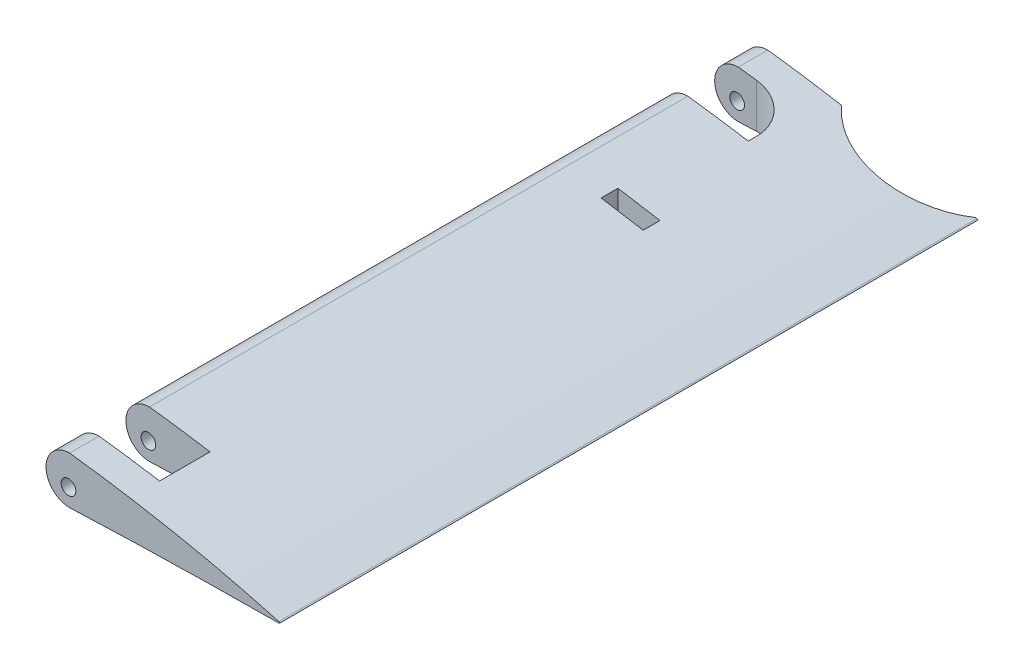
SolidWorks part; units mm, degrees
material "Balsa"
ref_plane "Front Plane" through (0, 0, 0) normal (0, 0, 1) x (1, 0, 0)
ref_plane "Top Plane" through (0, 0, 0) normal (0, 1, 0) x (1, 0, 0)
ref_plane "Right Plane" through (0, 0, 0) normal (1, 0, 0) x (0, 0, -1)
curve "曲線2"
  spline degree 3 poles (200, 0.26, 0) (196.6701, 1.1665, 0) (190.0264, 2.975, 0) (176.7171, 6.2635, 0) (160.0733, 9.8968, 0) (140.0541, 13.4784, 0) (120.0503, 16.4141, 0) (100.0354, 18.5082, 0) (80.0223, 19.8143, 0) (63.3151, 19.8275, 0) (49.9753, 18.9046, 0) (39.957, 17.689, 0) (29.917, 15.8963, 0) (21.5972, 13.7404, 0) (14.9301, 11.563, 0) (9.903, 9.5074, 0) (5.6136, 7.2843, 0) (1.8903, 4.6252, 0) (-1.3508, 0.3484, 0) (2.1476, -2.9224, 0) (5.7173, -4.2063, 0) (9.9686, -5.0729, 0) (14.9893, -5.5135, 0) (21.6639, -5.8253, 0) (30.0021, -5.8019, 0) (40.0043, -5.522, 0) (49.9995, -4.9891, 0) (63.3329, -4.3655, 0) (79.9968, -3.5653, 0) (100.0006, -2.8138, 0) (119.9979, -1.9794, 0) (139.9972, -1.2688, 0) (159.998, -0.746, 0) (176.6662, -0.4806, 0) (189.9997, -0.3058, 0) (196.6666, -0.2753, 0) (200, -0.26, 0) knots 0 0 0 0 0.025305 0.050488 0.10052 0.150191 0.199587 0.24874 0.297716 0.346601 0.371103 0.395726 0.42057 0.445825 0.458702 0.47192 0.485786 0.493461 0.506863 0.516148 0.522766 0.535269 0.547551 0.559786 0.584229 0.608681 0.633151 0.657622 0.706558 0.755482 0.804406 0.85332 0.902221 0.951113 0.975557 1 1 1 1
sketch "草圖4" plane through (0, 0, 0) normal (0, 0, 1) x (1, 0, 0)
  line L8 (26.3929, -5.7959) -> (118.9885, -5.7959) construction
  spline S1 degree 2 poles (120, 0.156) (120.5501, 0) (120, -0.156) knots 0 0 0 1 1 1
  spline S2 degree 3 poles (120, 0.156) (118.0021, 0.6999) (114.0158, 1.785) (106.0302, 3.7581) (96.044, 5.9381) (84.0324, 8.087) (72.0302, 9.8485) (60.0213, 11.1049) (48.0134, 11.8886) (37.9891, 11.8965) (29.9852, 11.3428) (23.9742, 10.6134) (17.9502, 9.5378) (12.9583, 8.2442) (8.9581, 6.9378) (5.9418, 5.7044) (3.3681, 4.3706) (1.1342, 2.7751) (-0.8105, 0.209) (1.2885, -1.7534) (3.4304, -2.5238) (5.9811, -3.0437) (8.9936, -3.3081) (12.9983, -3.4952) (18.0013, -3.4812) (24.0026, -3.3132) (29.9997, -2.9935) (37.9998, -2.6193) (47.9981, -2.1392) (60.0003, -1.6883) (71.9988, -1.1877) (83.9983, -0.7613) (95.9988, -0.4476) (105.9997, -0.2883) (113.9998, -0.1835) (118, -0.1652) (120, -0.156) knots 0 0 0 0 0.025305 0.050488 0.10052 0.150191 0.199587 0.24874 0.297716 0.346601 0.371103 0.395726 0.42057 0.445825 0.458702 0.47192 0.485786 0.493461 0.506863 0.516148 0.522766 0.535269 0.547551 0.559786 0.584229 0.608681 0.633151 0.657622 0.706558 0.755482 0.804406 0.85332 0.902221 0.951113 0.975557 1 1 1 1
extrude "填料-伸長1" add sketch "草圖4" along normal blind 185
sketch "草圖2" plane through (0, 0, 0) normal (0, 0, -1) x (-1, 0, 0)
  circle A0 centre (-25, 5) radius 3.25
  circle A1 centre (-50, 5) radius 3.25
  dimension "D1" = 6.5
  dimension "D2" = 25
  dimension "D3" = 25
  dimension "D4" = 5
extrude "除料-伸長1" cut sketch "草圖2" against normal through all
sketch "草圖3" plane through (0, 0, 0) normal (0, 1, 0) x (1, 0, 0)
  line L0 (120, 0) -> (-0.0337, 0) construction
  line L1 (70.275, -12) -> (120.275, -12)
  line L2 (70.275, -12) -> (70.275, -178)
  line L3 (70.275, -178) -> (120.275, -178)
  line L6 (-0.0337, -185) -> (120, -185) construction
  line L16 (120.275, -12) -> (166.4805, 19.3533)
  line L17 (166.4805, 19.3533) -> (-21.7711, 70.9334)
  line L18 (-21.7711, 70.9334) -> (-60.7316, -48.3616)
  line L19 (-60.7316, -48.3616) -> (-45.0232, -192.445)
  line L20 (-45.0232, -192.445) -> (84.8579, -230.5752)
  line L21 (84.8579, -230.5752) -> (139.8603, -200.5385)
  line L22 (139.8603, -200.5385) -> (120.275, -178)
  dimension "D1" = 12
  dimension "D3" = 7
extrude "除料-伸長2" cut sketch "草圖3" against normal through all and the other way through all
sketch "草圖5" plane through (0, 0, 178) normal (0, 0, 1) x (1, 0, 0)
  line L0 (70.275, 9.9794) -> (70.275, -1.2673)
  arc A0 (70.275, 9.9794) -> (70.275, -1.2673) centre (70.275, 4.356) ccw
extrude "填料-伸長2" add sketch "草圖5" against normal through all
sketch "草圖6" plane through (0, 0, 178) normal (0, 0, 1) x (1, 0, 0)
  circle A0 centre (70, 2.844) radius 1.75
  dimension "D1" = 3.5
  dimension "D2" = 50
  dimension "D3" = 3
extrude "除料-伸長3" cut sketch "草圖6" against normal through all
sketch "草圖7" plane through (0, 0, 0) normal (0, 1, 0) x (1, 0, 0)
  line L0 (120, -12) -> (70.275, -12) construction
  line L1 (79.6516, -57) -> (89.6516, -57)
  line L2 (79.6516, -57) -> (79.6516, -61)
  line L3 (79.6516, -61) -> (89.6516, -61)
  line L4 (89.6516, -57) -> (89.6516, -61)
  line L5 (64.6516, -12) -> (64.6516, -178) construction
  line L6 (70.275, -178) -> (120, -178) construction
  line L7 (64.6516, -19) -> (84.6516, -19)
  line L8 (64.6516, -19) -> (64.6516, -31)
  line L9 (64.6516, -31) -> (84.6516, -31)
  line L10 (84.6516, -19) -> (84.6516, -31)
  line L11 (64.6516, -171) -> (84.6516, -171)
  line L12 (64.6516, -171) -> (64.6516, -159)
  line L13 (64.6516, -159) -> (84.6516, -159)
  line L14 (84.6516, -171) -> (84.6516, -159)
  point P16 (0, 0)
  dimension "D1" = 4
  dimension "D2" = 10
  dimension "D3" = 45
  dimension "D4" = 25
  dimension "D5" = 20
  dimension "D6" = 7
  dimension "D7" = 7
  dimension "D8" = 12
extrude "除料-伸長4" cut sketch "草圖7" against normal through all and the other way through all
sketch "草圖9" plane through (0, 0, 0) normal (0, 1, 0) x (1, 0, 0)
  circle A0 centre (103.803, 2.085) radius 21.2881
  point P2 (105.9769, 2.5859)
  point P3 (103.803, 2.085)
extrude "除料-伸長6" cut sketch "草圖9" against normal through all and the other way through all
fillet "圓角1" radius 10 1 edges at (84.6516, 3.5807, 19)
